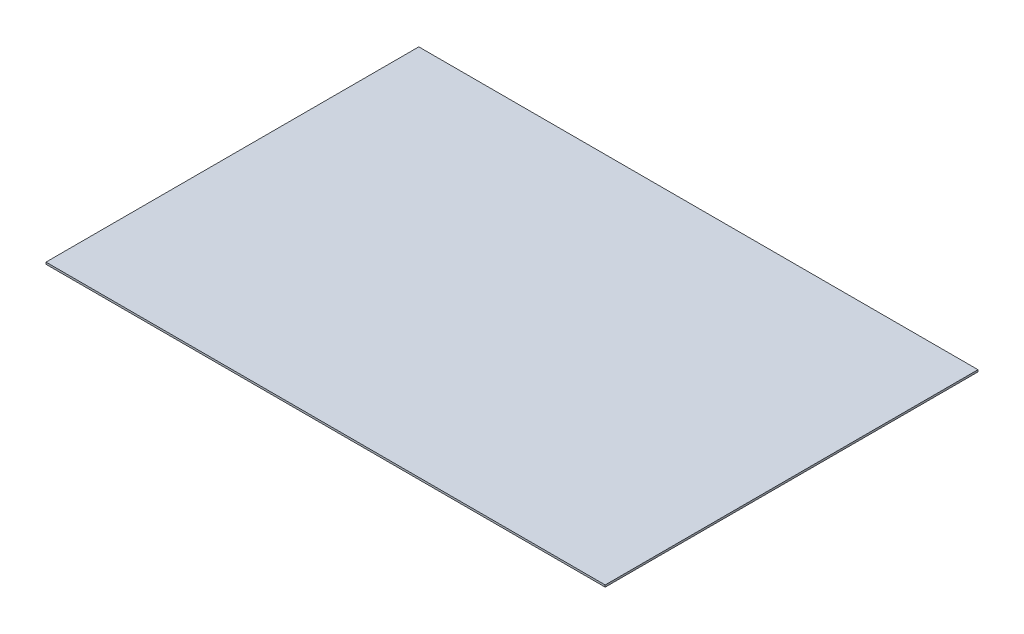
SolidWorks part; units mm, degrees
ref_plane "Front Plane" through (0, 0, 0) normal (0, 0, 1) x (1, 0, 0)
ref_plane "Top Plane" through (0, 0, 0) normal (0, 1, 0) x (1, 0, 0)
ref_plane "Right Plane" through (0, 0, 0) normal (1, 0, 0) x (0, 0, -1)
sketch "Sketch1" plane through (0, 0, 0) normal (0, 1, 0) x (1, 0, 0)
  line L1 (-914.4, -609.6) -> (914.4, -609.6)
  line L2 (-914.4, -609.6) -> (-914.4, 609.6)
  line L3 (-914.4, 609.6) -> (914.4, 609.6)
  line L4 (914.4, -609.6) -> (914.4, 609.6)
  line L5 (-914.4, -609.6) -> (914.4, 609.6) construction
  line L6 (-914.4, 609.6) -> (914.4, -609.6) construction
  point P0 (0, 0)
  dimension "D1" = 1828.8
  dimension "D2" = 1219.2
extrude "Boss-Extrude1" add sketch "Sketch1" along normal blind 6.35
